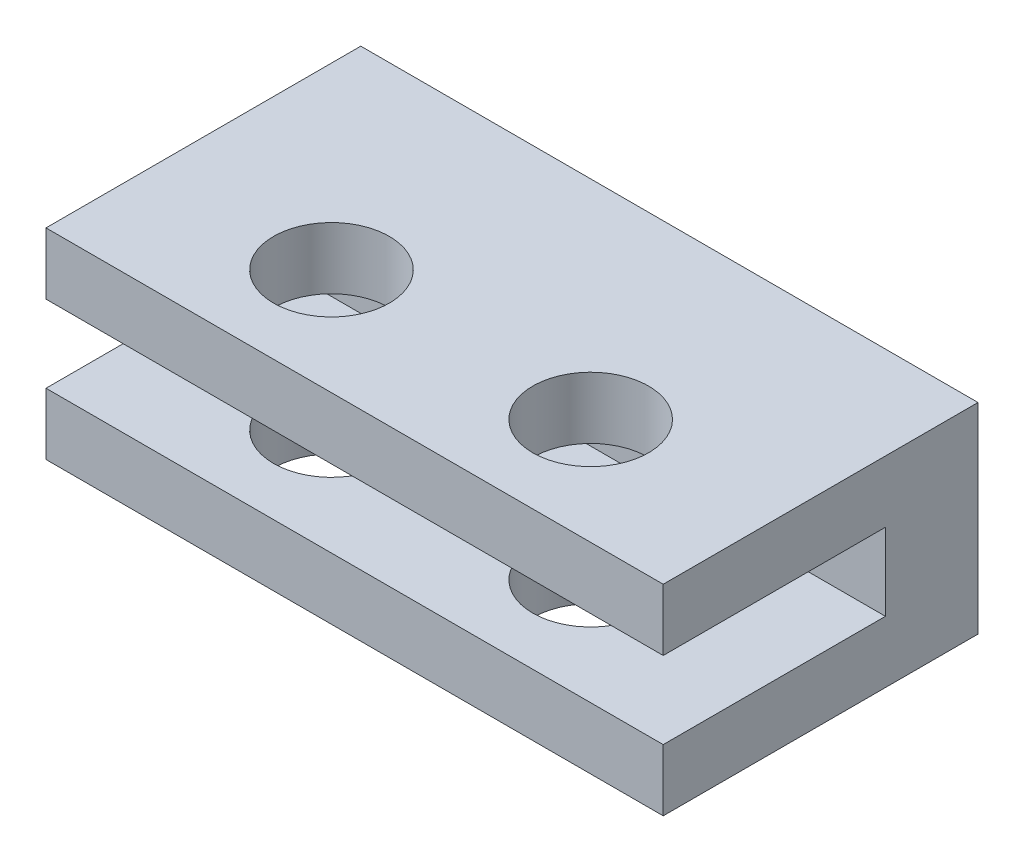
SolidWorks part; units mm, degrees
ref_plane "Front Plane" through (0, 0, 0) normal (0, 0, 1) x (1, 0, 0)
ref_plane "Top Plane" through (0, 0, 0) normal (0, 1, 0) x (1, 0, 0)
ref_plane "Right Plane" through (0, 0, 0) normal (1, 0, 0) x (0, 0, -1)
sketch "Sketch1" plane through (0, 0, 0) normal (0, 1, 0) x (1, 0, 0)
  line L1 (25.4, -12.954) -> (-25.4, -12.954)
  line L2 (25.4, -12.954) -> (25.4, 12.954)
  line L3 (25.4, 12.954) -> (-25.4, 12.954)
  line L4 (-25.4, -12.954) -> (-25.4, 12.954)
  line L5 (25.4, -12.954) -> (-25.4, 12.954) construction
  line L6 (25.4, 12.954) -> (-25.4, -12.954) construction
  point P0 (0, 0)
  dimension "D1" = 50.8
  dimension "D2" = 25.908
extrude "Boss-Extrude1" add sketch "Sketch1" along normal blind 5.08
sketch "Sketch2" plane through (0, 5.08, 0) normal (0, 1, 0) x (1, 0, 0)
  line L0 (25.4, -12.954) -> (25.4, 12.954) construction
  line L1 (-25.4, 12.954) -> (25.4, 12.954)
  line L2 (-25.4, 12.954) -> (-25.4, 5.334)
  line L3 (-25.4, 5.334) -> (25.4, 5.334)
  line L4 (25.4, 12.954) -> (25.4, 5.334)
  dimension "D1" = 7.62
extrude "Boss-Extrude2" add sketch "Sketch2" along normal blind 6.35
sketch "Sketch3" plane through (0, 11.43, 0) normal (0, 1, 0) x (1, 0, 0)
  line L1 (-25.4, 12.954) -> (25.4, 12.954)
  line L2 (-25.4, 12.954) -> (-25.4, 5.334)
  line L3 (-25.4, 5.334) -> (25.4, 5.334)
  line L4 (25.4, 12.954) -> (25.4, 5.334)
extrude "Boss-Extrude3" add sketch "Sketch3" along normal blind 5.08
sketch "Sketch4" plane through (0, 0, -5.334) normal (0, 0, 1) x (1, 0, 0)
  line L1 (-25.4, 16.51) -> (25.4, 16.51)
  line L2 (-25.4, 16.51) -> (-25.4, 11.43)
  line L3 (-25.4, 11.43) -> (25.4, 11.43)
  line L4 (25.4, 16.51) -> (25.4, 11.43)
  dimension "D1" = 5.08
extrude "Boss-Extrude4" add sketch "Sketch4" along normal blind 18.288
sketch "Sketch5" plane through (0, 16.51, 0) normal (0, 1, 0) x (1, 0, 0)
  line L0 (-25.4, 12.954) -> (-25.4, -12.954) construction
  line L1 (25.4, -12.954) -> (-25.4, -12.954) construction
  line L2 (25.4, -12.954) -> (25.4, 12.954) construction
  circle A0 centre (-10.668, -4.191) radius 4.7625
  circle A1 centre (10.668, -4.191) radius 4.7625
  dimension "D1" = 14.732
  dimension "D5" = 9.525
  dimension "D6" = 9.525
  dimension "D2" = 8.763
  dimension "D3" = 8.763
  dimension "D4" = 14.732
extrude "Cut-Extrude1" cut sketch "Sketch5" against normal through all
